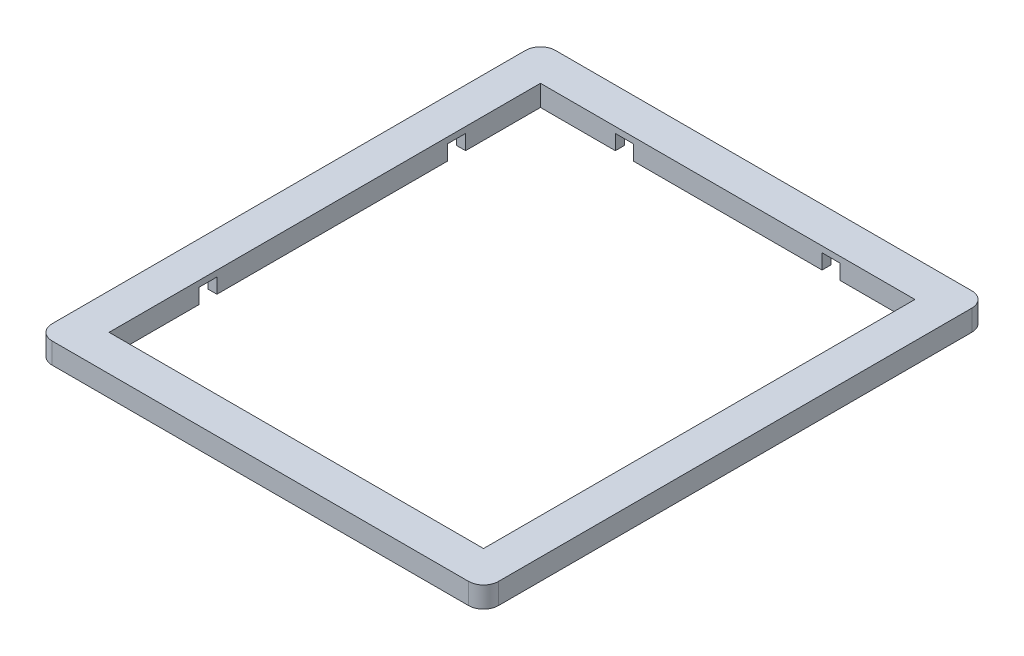
SolidWorks part; units mm, degrees
ref_plane "Front Plane" through (0, 0, 0) normal (0, 0, 1) x (1, 0, 0)
ref_plane "Top Plane" through (0, 0, 0) normal (0, 1, 0) x (1, 0, 0)
ref_plane "Right Plane" through (0, 0, 0) normal (1, 0, 0) x (0, 0, -1)
sketch "Sketch1" plane through (0, 0, 0) normal (0, 1, 0) x (1, 0, 0)
  line L0 (-122.389, 0) -> (137.7285, 0) construction
  line L1 (0, 82.8982) -> (0, -107.0496) construction
  line L2 (-71.312, 66.9817) -> (53.688, 66.9817)
  line L3 (53.688, 66.9817) -> (53.688, -77.0183)
  line L4 (53.688, -77.0183) -> (-71.312, -77.0183)
  line L5 (-71.312, -77.0183) -> (-71.312, 66.9817)
  line L6 (-83.312, 78.9817) -> (65.688, 78.9817)
  line L7 (65.688, 78.9817) -> (65.688, -89.0183)
  line L8 (65.688, -89.0183) -> (-83.312, -89.0183)
  line L9 (-83.312, -89.0183) -> (-83.312, 78.9817)
  dimension "D1" = 125
  dimension "D2" = 144
  dimension "D3" = 12
  dimension "D4" = 12
  dimension "D5" = 12
  dimension "D6" = 12
extrude "Boss-Extrude1" add sketch "Sketch1" along normal blind 7
fillet "Fillet1" radius 5 1 edges at (65.688, 3.5, 89.0183)
fillet "Fillet2" radius 5 1 edges at (-83.312, 3.5, 89.0183)
fillet "Fillet3" radius 5 1 edges at (-83.312, 3.5, -78.9817)
fillet "Fillet4" radius 5 1 edges at (65.688, 3.5, -78.9817)
sketch "Sketch4" plane through (0, 0, 0) normal (0, -1, 0) x (1, 0, 0)
  line L2 (-40.312, 80.0183) -> (-25.812, 80.0183)
  line L3 (-25.812, 80.0183) -> (-25.812, 84.5183)
  line L4 (-25.812, 84.5183) -> (-60.812, 84.5183)
  line L5 (-60.812, 84.5183) -> (-60.812, 80.0183)
  line L6 (-60.812, 80.0183) -> (-46.312, 80.0183)
  line L9 (22.688, 77.0183) -> (22.688, 80.0183)
  line L10 (53.688, 77.0183) -> (-71.312, 77.0183) construction
  line L11 (-46.312, 78.5183) -> (-40.312, 78.5183) construction
  line L14 (-43.312, 77.0183) -> (-8.812, 77.0183) construction
  line L15 (-46.312, 80.0183) -> (-46.312, 77.0183)
  line L16 (-46.312, 77.0183) -> (-40.312, 77.0183)
  line L17 (-40.312, 77.0183) -> (-40.312, 80.0183)
  line L18 (-8.812, 79.5665) -> (-8.812, 74.4701) construction
  line L19 (22.688, 80.0183) -> (8.188, 80.0183)
  line L20 (8.188, 80.0183) -> (8.188, 84.5183)
  line L21 (8.188, 84.5183) -> (43.188, 84.5183)
  line L22 (43.188, 84.5183) -> (43.188, 80.0183)
  line L23 (43.188, 80.0183) -> (28.688, 80.0183)
  line L24 (28.688, 80.0183) -> (28.688, 77.0183)
  line L25 (28.688, 77.0183) -> (22.688, 77.0183)
  line L26 (53.688, 47.0183) -> (56.688, 47.0183)
  line L27 (56.688, 47.0183) -> (56.688, 66.5183)
  line L28 (56.688, 66.5183) -> (61.188, 66.5183)
  line L29 (61.188, 66.5183) -> (61.188, 21.5183)
  line L30 (61.188, 21.5183) -> (56.688, 21.5183)
  line L31 (56.688, 21.5183) -> (56.688, 41.0183)
  line L32 (56.688, 41.0183) -> (53.688, 41.0183)
  line L33 (53.688, 41.0183) -> (53.688, 47.0183)
  line L34 (53.688, -35.9817) -> (56.688, -35.9817)
  line L35 (56.688, -35.9817) -> (56.688, -13.9817)
  line L36 (56.688, -13.9817) -> (61.188, -13.9817)
  line L37 (61.188, -13.9817) -> (61.188, -63.9817)
  line L38 (61.188, -63.9817) -> (56.688, -63.9817)
  line L39 (56.688, -63.9817) -> (56.688, -41.9817)
  line L40 (56.688, -41.9817) -> (53.688, -41.9817)
  line L41 (53.688, -41.9817) -> (53.688, -35.9817)
  line L44 (43.188, -69.9817) -> (43.188, -74.4817)
  line L45 (43.188, -74.4817) -> (8.188, -74.4817)
  line L46 (8.188, -74.4817) -> (8.188, -69.9817)
  line L47 (8.188, -69.9817) -> (22.688, -69.9817)
  line L48 (22.688, -69.9817) -> (22.688, -66.9817)
  line L50 (-40.312, -66.9817) -> (-40.312, -69.9817)
  line L51 (-40.312, -69.9817) -> (-25.812, -69.9817)
  line L52 (-25.812, -69.9817) -> (-25.812, -74.4817)
  line L53 (-25.812, -74.4817) -> (-60.812, -74.4817)
  line L54 (-60.812, -74.4817) -> (-60.812, -69.9817)
  line L55 (-60.812, -69.9817) -> (-46.312, -69.9817)
  line L56 (-46.312, -69.9817) -> (-46.312, -66.9817)
  line L57 (-46.312, -66.9817) -> (-40.312, -66.9817)
  line L58 (-71.312, -41.9817) -> (-74.312, -41.9817)
  line L59 (-74.312, -41.9817) -> (-74.312, -63.9817)
  line L60 (-74.312, -63.9817) -> (-78.812, -63.9817)
  line L61 (-78.812, -63.9817) -> (-78.812, -13.9817)
  line L62 (-78.812, -13.9817) -> (-74.312, -13.9817)
  line L63 (-74.312, -13.9817) -> (-74.312, -35.9817)
  line L64 (-74.312, -35.9817) -> (-71.312, -35.9817)
  line L65 (-71.312, -35.9817) -> (-71.312, -41.9817)
  line L66 (-71.312, 41.0183) -> (-74.312, 41.0183)
  line L67 (-74.312, 41.0183) -> (-74.312, 21.5183)
  line L68 (-74.312, 21.5183) -> (-78.812, 21.5183)
  line L69 (-78.812, 21.5183) -> (-78.812, 66.5183)
  line L70 (-78.812, 66.5183) -> (-74.312, 66.5183)
  line L71 (-74.312, 66.5183) -> (-74.312, 47.0183)
  line L72 (-74.312, 47.0183) -> (-71.312, 47.0183)
  line L73 (-71.312, 47.0183) -> (-71.312, 41.0183)
  line L74 (22.688, -66.9817) -> (28.688, -66.9817)
  line L75 (28.688, -66.9817) -> (28.688, -69.9817)
  line L76 (28.688, -69.9817) -> (43.188, -69.9817)
  point P3 (-43.312, 77.0183)
  point P17 (0, 0)
  point P18 (0, 0)
  point P19 (0, 0)
  point P20 (0, 0)
  point P24 (-8.812, 77.0183)
  point P134 (0, 0)
  point P137 (0, 0)
  point P138 (0, 0)
  point P139 (0, 0)
  point P140 (0, 0)
  point P141 (0, 0)
  point P142 (0, 0)
  point P143 (0, 0)
  point P144 (0, 0)
  point P145 (0, 0)
  point P146 (0, 0)
  point P147 (0, 0)
  point P148 (0, 0)
  point P149 (0, 0)
  point P150 (0, 0)
  point P151 (0, 0)
  point P152 (0, 0)
  point P153 (0, 0)
  point P154 (0, 0)
  point P155 (0, 0)
  point P156 (0, 0)
  dimension "D1" = 6
  dimension "D2" = 3
  dimension "D3" = 35
  dimension "34.45" = 34.5
  dimension "D4" = 4.5
extrude "Cut-Extrude1" cut sketch "Sketch4" against normal blind 3
sketch "Sketch5" plane through (-724.6859, -915.5936, -1334.8866) normal (0, 1, 0) x (1, 0, 0)
sketch "Sketch6" plane through (0, 0, 0) normal (0, -1, 0) x (1, 0, 0)
  circle A0 centre (-76.5798, 82.286) radius 1.325
  circle A1 centre (58.9558, 82.286) radius 1.325
  circle A2 centre (58.9558, -72.2495) radius 1.325
  circle A3 centre (-76.5798, -72.2495) radius 1.325
  dimension "D1" = 2.65
  dimension "D2" = 2.65
  dimension "D3" = 2.65
  dimension "D4" = 2.65
extrude "Cut-Extrude2" cut sketch "Sketch6" against normal blind 4
sketch "Sketch7" plane through (0, 3, 0) normal (0, -1, 0) x (1, 0, 0)
  line L0 (53.688, -35.9817) -> (56.688, -35.9817)
  line L1 (56.688, -35.9817) -> (56.688, -30.9817)
  line L2 (56.688, -13.9817) -> (56.688, -35.9817) construction
  line L3 (56.688, -30.9817) -> (61.188, -30.9817)
  line L4 (61.188, -63.9817) -> (61.188, -13.9817) construction
  line L5 (61.188, -30.9817) -> (61.188, -46.9817)
  line L6 (61.188, -63.9817) -> (61.188, -13.9817) construction
  line L7 (61.188, -46.9817) -> (56.688, -46.9817)
  line L8 (56.688, -41.9817) -> (56.688, -63.9817) construction
  line L9 (56.688, -46.9817) -> (56.688, -41.9817)
  line L10 (56.688, -41.9817) -> (53.688, -41.9817)
  line L11 (53.688, -41.9817) -> (53.688, -35.9817)
  line L12 (53.688, 47.0183) -> (56.688, 47.0183)
  line L13 (56.688, 47.0183) -> (56.688, 52.0183)
  line L14 (56.688, 52.0183) -> (61.188, 52.0183)
  line L15 (61.188, 52.0183) -> (61.188, 36.0183)
  line L16 (61.188, 36.0183) -> (56.688, 36.0183)
  line L17 (56.688, 36.0183) -> (56.688, 41.0183)
  line L18 (56.688, 41.0183) -> (53.688, 41.0183)
  line L19 (53.688, 41.0183) -> (53.688, 47.0183)
  line L20 (28.688, 77.0183) -> (28.688, 80.0183)
  line L21 (28.688, 80.0183) -> (33.688, 80.0183)
  line L22 (28.688, 80.0183) -> (43.188, 80.0183) construction
  line L23 (33.688, 80.0183) -> (33.688, 84.5183)
  line L24 (43.188, 84.5183) -> (8.188, 84.5183) construction
  line L25 (33.688, 84.5183) -> (17.688, 84.5183)
  line L26 (17.688, 84.5183) -> (17.688, 80.0183)
  line L27 (8.188, 80.0183) -> (22.688, 80.0183) construction
  line L28 (17.688, 80.0183) -> (22.688, 80.0183)
  line L29 (22.688, 80.0183) -> (22.688, 77.0183)
  line L30 (22.688, 77.0183) -> (28.688, 77.0183)
  line L31 (-40.312, 77.0183) -> (-40.312, 80.0183)
  line L32 (-40.312, 80.0183) -> (-35.312, 80.0183)
  line L33 (-35.312, 80.0183) -> (-35.312, 84.5183)
  line L34 (-35.312, 84.5183) -> (-51.312, 84.5183)
  line L35 (-51.312, 84.5183) -> (-51.312, 80.0183)
  line L36 (-51.312, 80.0183) -> (-46.312, 80.0183)
  line L37 (-46.312, 80.0183) -> (-46.312, 77.0183)
  line L38 (-46.312, 77.0183) -> (-40.312, 77.0183)
  line L39 (-71.312, 47.0183) -> (-74.312, 47.0183)
  line L40 (-74.312, 47.0183) -> (-74.312, 52.0183)
  line L41 (-74.312, 47.0183) -> (-74.312, 66.5183) construction
  line L42 (-74.312, 52.0183) -> (-78.812, 52.0183)
  line L43 (-78.812, 66.5183) -> (-78.812, 21.5183) construction
  line L44 (-78.812, 52.0183) -> (-78.812, 36.0183)
  line L45 (-78.812, 66.5183) -> (-78.812, 21.5183) construction
  line L46 (-78.812, 36.0183) -> (-74.312, 36.0183)
  line L47 (-74.312, 21.5183) -> (-74.312, 41.0183) construction
  line L48 (-74.312, 36.0183) -> (-74.312, 41.0183)
  line L49 (-74.312, 41.0183) -> (-71.312, 41.0183)
  line L50 (-71.312, 41.0183) -> (-71.312, 47.0183)
  line L51 (-71.312, -35.9817) -> (-74.312, -35.9817)
  line L52 (-74.312, -35.9817) -> (-74.312, -30.9817)
  line L53 (-74.312, -35.9817) -> (-74.312, -13.9817) construction
  line L54 (-74.312, -30.9817) -> (-78.812, -30.9817)
  line L55 (-78.812, -13.9817) -> (-78.812, -63.9817) construction
  line L56 (-78.812, -30.9817) -> (-78.812, -46.9817)
  line L57 (-78.812, -13.9817) -> (-78.812, -63.9817) construction
  line L58 (-78.812, -46.9817) -> (-74.312, -46.9817)
  line L59 (-74.312, -63.9817) -> (-74.312, -41.9817) construction
  line L60 (-74.312, -46.9817) -> (-74.312, -41.9817)
  line L61 (-74.312, -41.9817) -> (-71.312, -41.9817)
  line L62 (-71.312, -41.9817) -> (-71.312, -35.9817)
  line L63 (-46.312, -66.9817) -> (-46.312, -69.9817)
  line L64 (-46.312, -69.9817) -> (-51.312, -69.9817)
  line L65 (-46.312, -69.9817) -> (-60.812, -69.9817) construction
  line L66 (-51.312, -69.9817) -> (-51.312, -74.4817)
  line L67 (-60.812, -74.4817) -> (-25.812, -74.4817) construction
  line L68 (-51.312, -74.4817) -> (-35.312, -74.4817)
  line L69 (-35.312, -74.4817) -> (-35.312, -69.9817)
  line L70 (-25.812, -69.9817) -> (-40.312, -69.9817) construction
  line L71 (-35.312, -69.9817) -> (-40.312, -69.9817)
  line L72 (-40.312, -69.9817) -> (-40.312, -66.9817)
  line L73 (-40.312, -66.9817) -> (-46.312, -66.9817)
  line L74 (22.688, -66.9817) -> (22.688, -69.9817)
  line L75 (22.688, -69.9817) -> (17.688, -69.9817)
  line L76 (22.688, -69.9817) -> (8.188, -69.9817) construction
  line L77 (17.688, -69.9817) -> (17.688, -74.4817)
  line L78 (8.188, -74.4817) -> (43.188, -74.4817) construction
  line L79 (17.688, -74.4817) -> (33.688, -74.4817)
  line L80 (33.688, -74.4817) -> (33.688, -69.9817)
  line L81 (43.188, -69.9817) -> (28.688, -69.9817) construction
  line L82 (33.688, -69.9817) -> (28.688, -69.9817)
  line L83 (28.688, -69.9817) -> (28.688, -66.9817)
  line L84 (28.688, -66.9817) -> (22.688, -66.9817)
  dimension "D1" = 5
  dimension "D2" = 5
  dimension "D3" = 5
  dimension "D4" = 5
extrude "Cut-Extrude3" cut sketch "Sketch7" against normal blind 2
